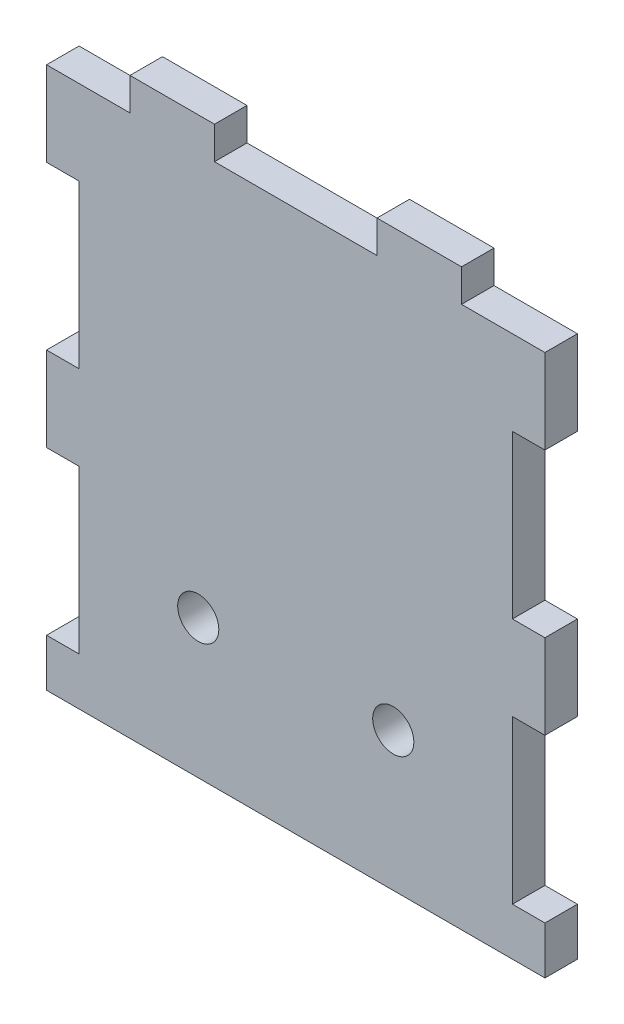
SolidWorks part; units mm, degrees
material "Oak"
ref_plane "Front Plane" through (0, 0, 0) normal (0, 0, 1) x (1, 0, 0)
ref_plane "Top Plane" through (0, 0, 0) normal (0, 1, 0) x (1, 0, 0)
ref_plane "Right Plane" through (0, 0, 0) normal (1, 0, 0) x (0, 0, -1)
sketch "Sketch1" plane through (0, 0, 0) normal (0, 0, 1) x (1, 0, 0)
  line L1 (-40.9935, 16.542) -> (5.0065, 16.542)
  line L2 (-40.9935, 16.542) -> (-40.9935, -33.458)
  line L3 (-40.9935, -33.458) -> (5.0065, -33.458)
  line L4 (5.0065, 16.542) -> (5.0065, -33.458)
  dimension "D1" = 50
  dimension "D2" = 46
extrude "Boss-Extrude1" add sketch "Sketch1" along normal blind 3
sketch "Sketch2" plane through (0, 0, 3) normal (0, 0, 1) x (1, 0, 0)
  line L0 (-40.9935, 16.542) -> (-40.9935, -33.458) construction
  line L1 (-40.9935, 8.742) -> (-37.9935, 8.742)
  line L2 (-40.9935, 8.742) -> (-40.9935, -6.258)
  line L3 (-40.9935, -6.258) -> (-37.9935, -6.258)
  line L4 (-37.9935, 8.742) -> (-37.9935, -6.258)
  line L5 (5.0065, 16.542) -> (-40.9935, 16.542) construction
  line L6 (5.0065, -33.458) -> (5.0065, 16.542) construction
  line L7 (5.0065, 8.742) -> (2.0065, 8.742)
  line L8 (5.0065, 8.742) -> (5.0065, -6.258)
  line L9 (5.0065, -6.258) -> (2.0065, -6.258)
  line L10 (2.0065, 8.742) -> (2.0065, -6.258)
  point P8 (-39.4935, 8.742)
  dimension "D1" = 3
  dimension "D2" = 7.8
  dimension "D3" = 15
  dimension "D4" = 3
  dimension "D5" = 7.8
  dimension "D6" = 15
extrude "Cut-Extrude1" cut sketch "Sketch2" against normal through all
pattern_linear "LPattern1" count 3 spacing 22.8 along (0, -1, 0) of "Cut-Extrude1"
sketch "Sketch3" plane through (0, 16.542, 0) normal (0, 1, 0) x (1, 0, 0)
  line L0 (5.0065, 0) -> (-40.9935, 0) construction
  line L1 (-33.2935, 0) -> (-25.4935, 0)
  line L2 (-33.2935, 0) -> (-33.2935, -3)
  line L3 (-33.2935, -3) -> (-25.4935, -3)
  line L4 (-25.4935, 0) -> (-25.4935, -3)
  line L5 (5.0065, -3) -> (-40.9935, -3) construction
  line L6 (-40.9935, -3) -> (-40.9935, 0) construction
  point P8 (-25.4935, -1.5)
  dimension "D1" = 7.8
  dimension "D2" = 7.7
extrude "Boss-Extrude2" add sketch "Sketch3" along normal blind 3
pattern_linear "LPattern2" count 2 spacing 22.8 along (1, 0, 0) of "Boss-Extrude2"
hole_wizard "#6 Clearance Hole1" positions "Sketch4" profile "Sketch5" hole size "#6" standard "ANSI Inch" end condition through all
sketch "Sketch4" plane through (0, 0, 3) normal (0, 0, 1) x (1, 0, 0)
  point P0 (-8.9935, -20.658)
  point P3 (-26.9935, -20.658)
sketch "Sketch5" plane through (-8.9935, -20.658, 3) normal (1, 0, 0) x (0, -1, 0)
  line L0 (0, 0) -> (0, 3)
  line L1 (0, 3) -> (1.8986, 3)
  line L2 (1.8986, 3) -> (1.8986, 0)
  line L5 (1.8986, 0) -> (0, 0)
  line L11 (0, -6.35) -> (0, 107.95) construction
  dimension "Thru Hole Dia." = 3.7973
  dimension "Thru Hole Depth" = 3
